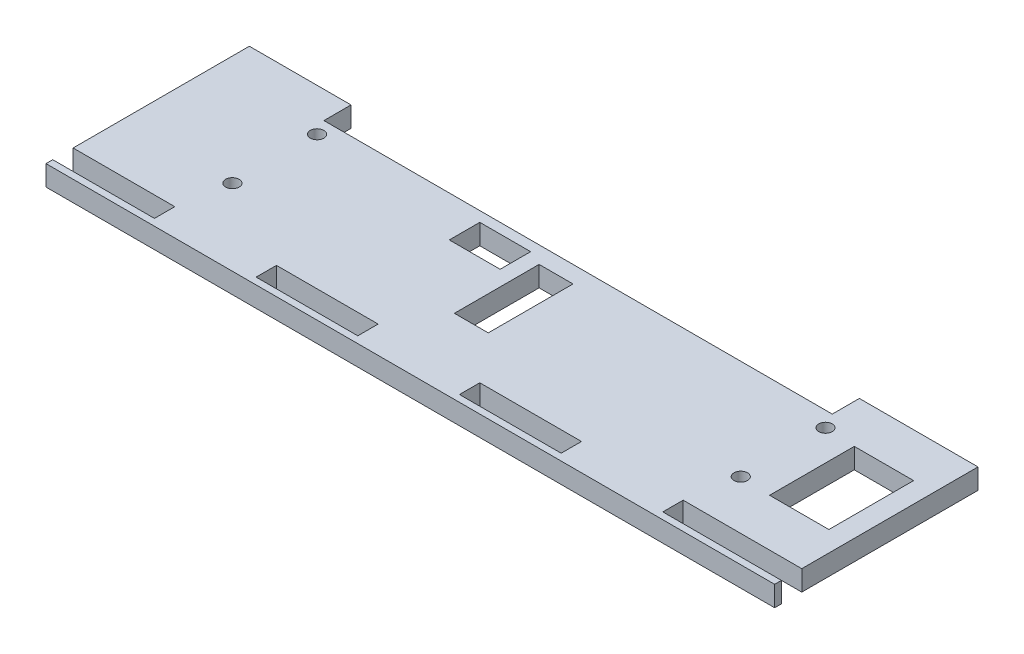
SolidWorks part; units mm, degrees
ref_plane "Спереди" through (0, 0, 0) normal (0, 0, 1) x (1, 0, 0)
ref_plane "Сверху" through (0, 0, 0) normal (0, 1, 0) x (1, 0, 0)
ref_plane "Справа" through (0, 0, 0) normal (1, 0, 0) x (0, 0, -1)
sketch "Эскиз1" plane through (0, 0, 0) normal (0, 1, 0) x (1, 0, 0)
  line L0 (0, 0) -> (1, 0) construction
  line L1 (-107.5, -33) -> (-107.5, -27) construction
  line L2 (-107.5, 25) -> (-107.5, -27)
  line L3 (107.5, -27) -> (107.5, -33) construction
  line L4 (107.5, 25) -> (107.5, -27)
  line L5 (72.5, 25) -> (107.5, 25)
  line L7 (-107.5, 25) -> (-77.3368, 25)
  line L8 (-77.5, 25) -> (-77.5, 17)
  line L11 (-77.5, 17) -> (72.5, 17)
  line L12 (72.5, 25) -> (72.5, 17)
  line L17 (-28.5, 14) -> (-13.5, 14)
  line L18 (-28.5, 14) -> (-28.5, 5)
  line L19 (-28.5, 5) -> (-13.5, 5)
  line L20 (-13.5, 14) -> (-13.5, 5)
  line L21 (1, -13) -> (-9, -13)
  line L22 (1, -13) -> (1, 12)
  line L23 (101.5, -13) -> (84, -13)
  line L24 (101.5, -13) -> (101.5, 12)
  line L25 (101.5, 12) -> (84, 12)
  line L26 (84, -13) -> (84, 12)
  line L27 (1, 12) -> (-9, 12)
  line L28 (-9, -13) -> (-9, 12)
  line L31 (-107.5, -35) -> (107.5, -35)
  line L33 (-107.5, -27) -> (-77.5, -27)
  line L34 (107.5, -33) -> (107.5, -35)
  line L35 (-107.5, -33) -> (-77.5, -33)
  line L37 (12.5, -27) -> (42.5, -27)
  line L38 (-77.5, -27) -> (-77.5, -33)
  line L39 (12.5, -33) -> (42.5, -33)
  line L40 (-47.5, -27) -> (-47.5, -33)
  line L42 (-47.5, -33) -> (-17.5, -33)
  line L43 (-17.5, -27) -> (-17.5, -33)
  line L44 (72.5, -27) -> (107.5, -27)
  line L46 (-107.5, -33) -> (-107.5, -35)
  line L47 (12.5, -27) -> (12.5, -33)
  line L51 (42.5, -27) -> (42.5, -33)
  line L55 (72.5, -27) -> (72.5, -33)
  line L57 (-47.5, -27) -> (-17.5, -27)
  line L59 (72.5, -33) -> (107.5, -33)
  line L60 (-47.5, -27) -> (-47.5, -33) [skipped]
  line L61 (-17.5, -27) -> (-17.5, -33) [skipped]
  line L62 (12.5, -27) -> (12.5, -33) [skipped]
  line L63 (42.5, -27) -> (42.5, -33) [skipped]
  circle A0 centre (-75, 12.5) radius 2
  circle A1 centre (-75, -12.5) radius 2
  circle A2 centre (75, -12.5) radius 2
  circle A3 centre (75, 12.5) radius 2
  point P0 (0, 0)
  dimension "D5" = 8
  dimension "D3" = 32.5
  dimension "D4" = 52
  dimension "D24" = 4
  dimension "D25" = 4
  dimension "D38" = 4
  dimension "D39" = 11
  dimension "D1" = 215
  dimension "D6" = 30
  dimension "D7" = 25
  dimension "D8" = 52
  dimension "D9" = 15
  dimension "D10" = 9
  dimension "D11" = 25
  dimension "D12" = 25
  dimension "D13" = 17.5
  dimension "D14" = 83
  dimension "D15" = 10
  dimension "D16" = 107.5
  dimension "D17" = 6
  dimension "D18" = 2
  dimension "D19" = 150
  dimension "D20" = 12.5
  dimension "D22" = 32.5
  dimension "D23" = 14.5
  dimension "D26" = 150
  dimension "D27" = 8
  dimension "D28" = 2
  dimension "D29" = 30
  dimension "D30" = 30
  dimension "D31" = 30
  dimension "D32" = 30
  dimension "D33" = 30
  dimension "D34" = 30
  dimension "D35" = 6
  dimension "D36" = 6
  dimension "D37" = 30
  dimension "D40" = 79
  dimension "D41" = 98.5
  dimension "D42" = 13
  dimension "D43" = 25
  dimension "D21" = 5
extrude "Бобышка-Вытянуть1" add sketch "Эскиз1" along normal blind 6
